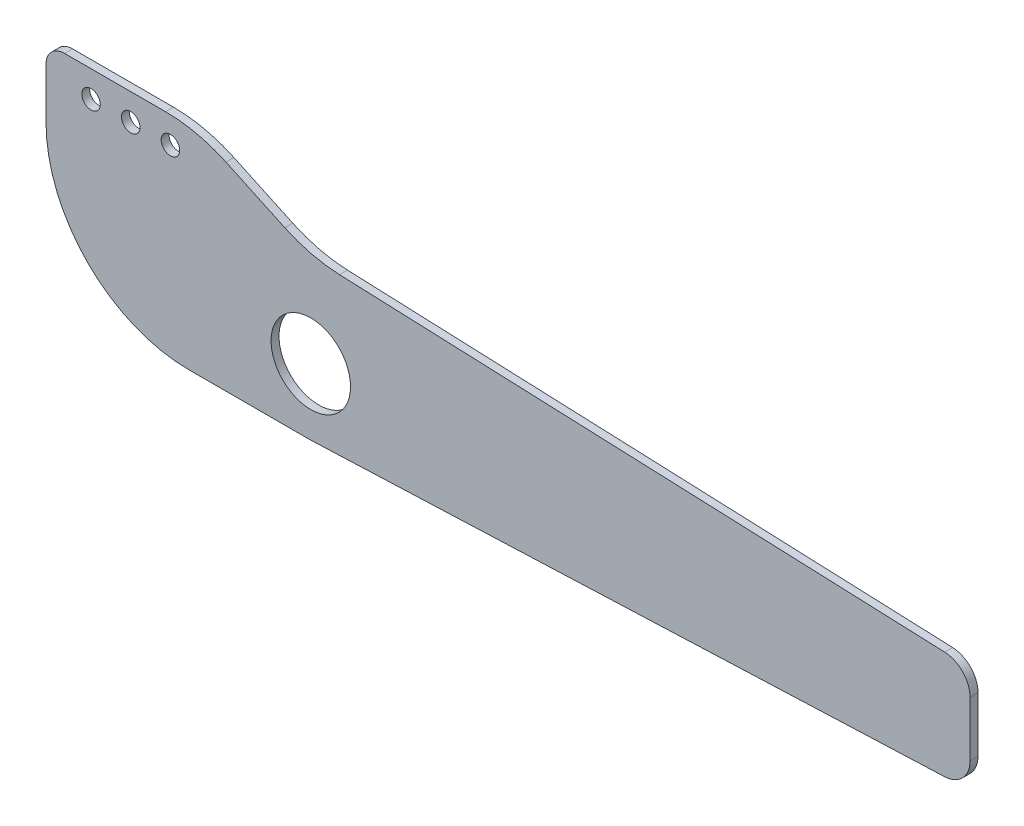
SolidWorks part; units mm, degrees
ref_plane "Plan de face" through (0, 0, 0) normal (0, 0, 1) x (1, 0, 0)
ref_plane "Plan de dessus" through (0, 0, 0) normal (0, 1, 0) x (1, 0, 0)
ref_plane "Plan de droite" through (0, 0, 0) normal (1, 0, 0) x (0, 0, -1)
sketch "Esquisse1" plane through (0, 0, 0) normal (0, 0, 1) x (1, 0, 0)
  line L0 (0, 0) -> (0, 60)
  line L2 (348.9783, 50) -> (348.9783, 10)
  line L4 (0, 60) -> (345.6458, 60) construction
  line L5 (0, 0) -> (349.1752, 0) construction
  line L6 (0, 60) -> (100, 60)
  line L7 (100, 60) -> (348.9783, 50)
  line L8 (348.9783, 10) -> (100, 0)
  line L9 (100, 0) -> (0, 0)
  dimension "D1" = 60
  dimension "D2" = 40
  dimension "D3" = 100
  dimension "D4" = 100
  dimension "D5" = 2.3
  dimension "D6" = 2.3
extrude "Boss.-Extru.1" add sketch "Esquisse1" along normal blind 3
sketch "Esquisse2" plane through (0, 0, 3) normal (0, 0, 1) x (1, 0, 0)
  line L0 (0, 30) -> (348.9783, 30) construction
  line L1 (0, 60) -> (0, 0) construction
  line L2 (348.9783, 10) -> (348.9783, 50) construction
  circle A0 centre (100, 25) radius 15
  dimension "D1" = 30
  dimension "D2" = 5
  dimension "D3" = 100
extrude "Enlèv. mat.-Extru.1" cut sketch "Esquisse2" against normal blind 3
sketch "Esquisse3" plane through (0, 60, 0) normal (0, 1, 0) x (1, 0, 0)
  line L1 (0, 0) -> (100, 0)
  line L2 (0, 0) -> (0, -3)
  line L3 (0, -3) -> (100, -3)
  line L4 (100, 0) -> (100, -3)
extrude "Boss.-Extru.2" add sketch "Esquisse3" along normal blind 20
sketch "Esquisse4" plane through (0, 0, 3) normal (0, 0, 1) x (1, 0, 0)
  line L0 (100, 80) -> (100, 60) construction
  line L1 (0, 80) -> (100, 80) construction
  circle A0 centre (47, 70) radius 3.5
  circle A1 centre (32, 70) radius 3.5
  circle A2 centre (17, 70) radius 3.5
  dimension "D2" = 10
  dimension "D3" = 7
  dimension "D5" = 7
  dimension "D6" = 7
  dimension "D8" = 83
  dimension "D1" = 53
  dimension "D4" = 68
  dimension "D7" = 10
  dimension "D9" = 10
extrude "Enlèv. mat.-Extru.2" cut sketch "Esquisse4" against normal blind 3
sketch "Esquisse5" plane through (0, 0, 3) normal (0, 0, 1) x (1, 0, 0)
  line L0 (100, 60) -> (57.1099, 80)
  line L1 (0, 80) -> (100, 80) construction
  line L2 (57.1099, 80) -> (100, 80)
  line L3 (100, 80) -> (100, 60)
extrude "Enlèv. mat.-Extru.3" cut sketch "Esquisse5" against normal blind 3
fillet "Congé1" radius 54 2 edges at (100, 60, 1.5) (57.1099, 80, 1.5)
fillet "Congé3" radius 54 1 edges at (0, 0, 1.5)
fillet "Congé4" radius 10 2 edges at (348.9783, 50, 1.5) (348.9783, 10, 1.5)
fillet "Congé5" radius 7 1 edges at (0, 80, 1.5)
